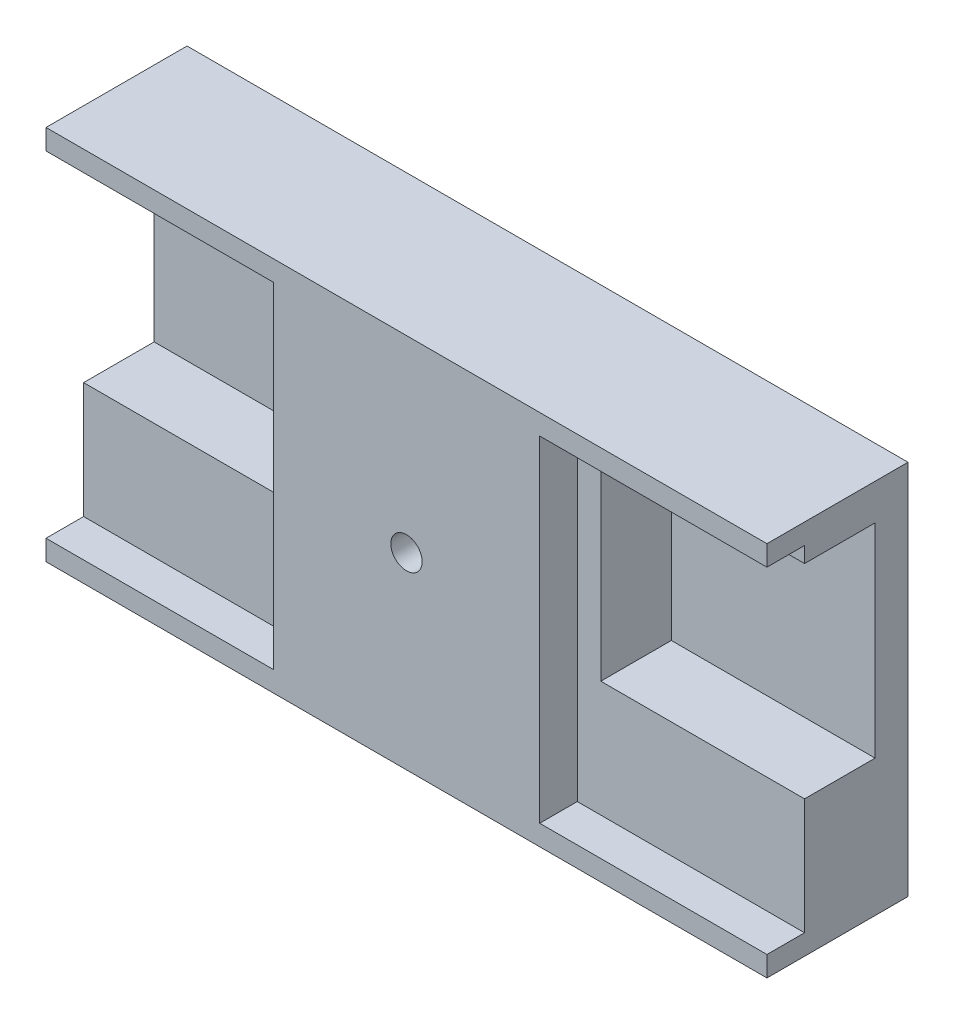
SolidWorks part; units mm, degrees
material "ABS"
ref_plane "Plan de face" through (0, 0, 0) normal (0, 0, 1) x (1, 0, 0)
ref_plane "Plan de dessus" through (0, 0, 0) normal (0, 1, 0) x (1, 0, 0)
ref_plane "Plan de droite" through (0, 0, 0) normal (1, 0, 0) x (0, 0, -1)
sketch "Esquisse1" plane through (0, 0, 0) normal (0, 0, 1) x (1, 0, 0)
  line L1 (-23.1069, -3.1195) -> (22.8931, -3.1195)
  line L2 (-23.1069, -3.1195) -> (-23.1069, 20.8805)
  line L3 (-23.1069, 20.8805) -> (22.8931, 20.8805)
  line L4 (22.8931, -3.1195) -> (22.8931, 20.8805)
  dimension "D1" = 46
  dimension "D2" = 24
extrude "Boss.-Extru.1" add sketch "Esquisse1" along normal blind 9
sketch "Esquisse2" plane through (0, 0, 9) normal (0, 0, 1) x (1, 0, 0)
  line L1 (-0.1069, 20.8805) -> (-0.1069, 8.8101) construction
  line L2 (22.8931, 20.8805) -> (-23.1069, 20.8805) construction
  line L3 (-23.1069, 8.8805) -> (4.5152, 8.8805) construction
  line L4 (-23.1069, 20.8805) -> (-23.1069, -3.1195) construction
  circle A0 centre (-0.1069, 8.8805) radius 1
  dimension "D1" = 2
extrude "Enlèv. mat.-Extru.1" cut sketch "Esquisse2" against normal blind 19
sketch "Esquisse3" plane through (0, 0, 9) normal (0, 0, 1) x (1, 0, 0)
  line L0 (-0.1069, 8.8805) -> (-0.1069, 23.9189) construction
  line L1 (-24.2069, 19.5805) -> (-8.6069, 19.5805)
  line L2 (-24.2069, 19.5805) -> (-24.2069, -1.8195)
  line L3 (-24.2069, -1.8195) -> (-8.6069, -1.8195)
  line L4 (-8.6069, 19.5805) -> (-8.6069, -1.8195)
  line L5 (-0.1069, 8.8805) -> (-14.2986, 8.8805) construction
  line L6 (23.9931, -1.8195) -> (8.3931, -1.8195)
  line L7 (23.9931, 19.5805) -> (23.9931, -1.8195)
  line L8 (23.9931, 19.5805) -> (8.3931, 19.5805)
  line L9 (8.3931, 19.5805) -> (8.3931, -1.8195)
  dimension "D1" = 8.5
  dimension "D2" = 15.6
  dimension "D3" = 21.4
extrude "Enlèv. mat.-Extru.2" cut sketch "Esquisse3" against normal blind 2.4
sketch "Esquisse4" plane through (0, 0, 6.6) normal (0, 0, 1) x (1, 0, 0)
  line L0 (-0.1069, 8.8805) -> (-0.1069, 26.4956) construction
  line L1 (-24.1069, 18.5805) -> (-10.1069, 18.5805)
  line L2 (-24.1069, 18.5805) -> (-24.1069, 5.5805)
  line L3 (-24.1069, 5.5805) -> (-10.1069, 5.5805)
  line L4 (-10.1069, 18.5805) -> (-10.1069, 5.5805)
  line L5 (9.8931, 18.5805) -> (9.8931, 5.5805)
  line L6 (23.8931, 5.5805) -> (9.8931, 5.5805)
  line L7 (23.8931, 18.5805) -> (23.8931, 5.5805)
  line L8 (23.8931, 18.5805) -> (9.8931, 18.5805)
  line L9 (-8.6069, 19.5805) -> (-23.1069, 19.5805) construction
  dimension "D1" = 14
  dimension "D2" = 13
  dimension "D3" = 10
  dimension "D4" = 1
extrude "Enlèv. mat.-Extru.3" cut sketch "Esquisse4" against normal blind 4.5
